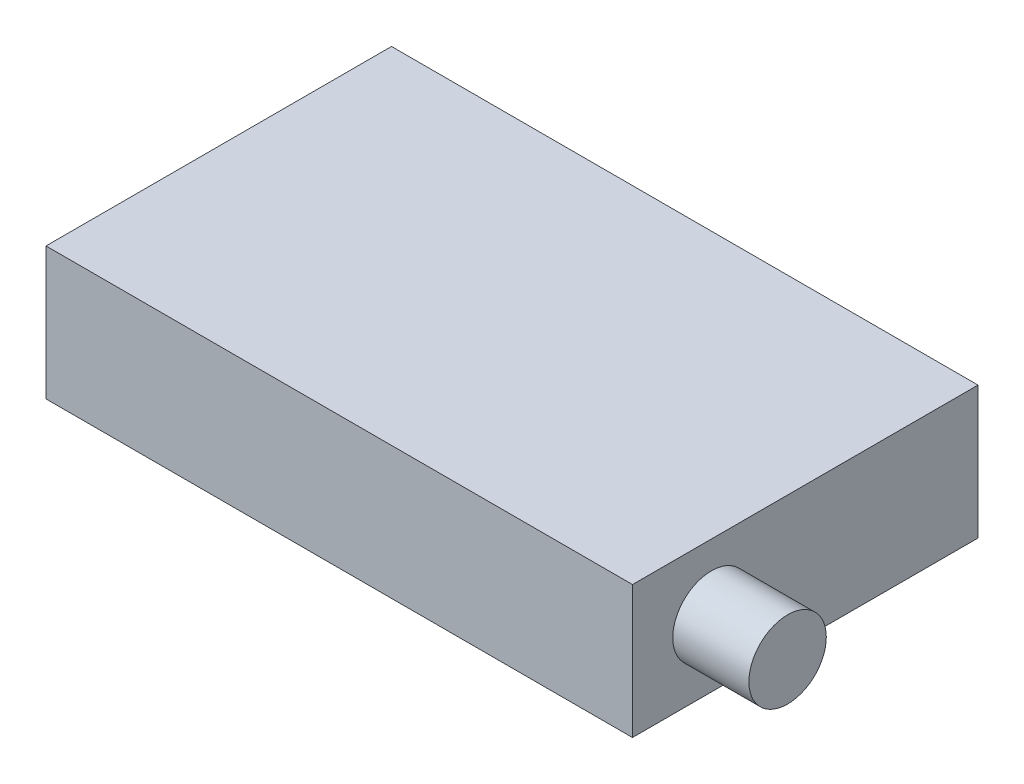
SolidWorks part; units mm, degrees
ref_plane "Front Plane" through (0, 0, 0) normal (0, 0, 1) x (1, 0, 0)
ref_plane "Top Plane" through (0, 0, 0) normal (0, 1, 0) x (1, 0, 0)
ref_plane "Right Plane" through (0, 0, 0) normal (1, 0, 0) x (0, 0, -1)
sketch "Sketch1" plane through (0, 0, 0) normal (0, 1, 0) x (1, 0, 0)
  line L0 (-55, 0) -> (55, 0) construction
  line L1 (-23.68, 13.95) -> (23.68, 13.95)
  line L2 (-23.68, 13.95) -> (-23.68, -13.95)
  line L3 (-23.68, -13.95) -> (23.68, -13.95)
  line L4 (23.68, 13.95) -> (23.68, -13.95)
  line L6 (0, -55) -> (0, 55) construction
  point P4 (23.68, 0)
  point P8 (0, 13.95)
  dimension "D1" = 47.36
  dimension "D2" = 27.9
extrude "Boss-Extrude1" add sketch "Sketch1" along normal mid plane 10.7
sketch "Sketch2" plane through (23.68, 0, 0) normal (1, 0, 0) x (0, 0, -1)
  line L0 (-13.95, 5.35) -> (-13.95, -5.35) construction
  line L1 (15.345, 0) -> (-15.345, 0) construction
  circle A0 centre (-7.575, 0) radius 3.125
  dimension "D1" = 6.25
  dimension "D2" = 6.375
extrude "Boss-Extrude2" add sketch "Sketch2" along normal blind 6.15
sketch "Sketch3" plane through (-23.68, 0, 0) normal (-1, 0, 0) x (0, 0, 1)
  line L0 (-13.95, -5.35) -> (13.95, -5.35) construction
  line L1 (-10.25, 0.95) -> (0.95, 0.95)
  line L2 (-10.25, 0.95) -> (-10.25, -4.05)
  line L3 (-10.25, -4.05) -> (0.95, -4.05)
  line L4 (0.95, 0.95) -> (0.95, -4.05)
  line L5 (-13.95, 5.35) -> (-13.95, -5.35) construction
  dimension "D1" = 11.2
  dimension "D2" = 1.3
  dimension "D3" = 3.7
  dimension "D4" = 5
extrude "Cut-Extrude1" cut sketch "Sketch3" against normal blind 1
sketch "Sketch5" plane through (-23.68, 0, 0) normal (-1, 0, 0) x (0, 0, 1)
  line L1 (0.95, 0.95) -> (9.85, 0.95)
  line L2 (0.95, 0.95) -> (0.95, -2.25)
  line L3 (0.95, -2.25) -> (9.85, -2.25)
  line L4 (9.85, 0.95) -> (9.85, -2.25)
  dimension "D1" = 3.2
  dimension "D2" = 8.9
extrude "Cut-Extrude2" cut sketch "Sketch5" against normal blind 1
